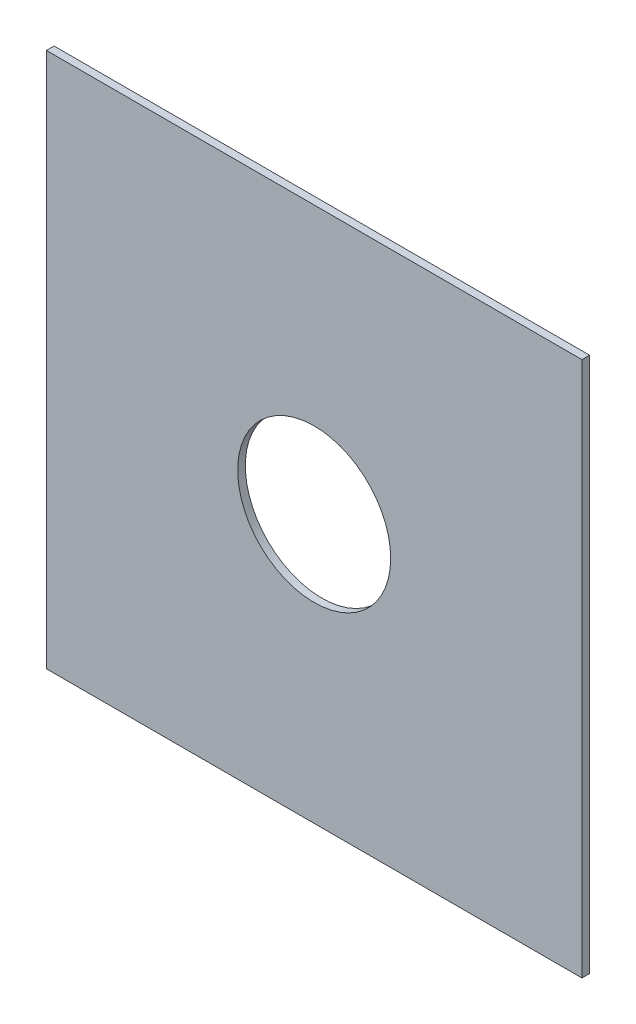
SolidWorks part; units mm, degrees
ref_plane "前视基准面" through (0, 0, 0) normal (0, 0, 1) x (1, 0, 0)
ref_plane "上视基准面" through (0, 0, 0) normal (0, 1, 0) x (1, 0, 0)
ref_plane "右视基准面" through (0, 0, 0) normal (1, 0, 0) x (0, 0, -1)
sketch "草图1" plane through (0, 0, 0) normal (0, 0, 1) x (1, 0, 0)
  line L0 (-49.8973, -319.1589) -> (650.1027, -319.1589) construction
  line L1 (-49.8973, 30.8411) -> (650.1027, 30.8411)
  line L2 (-49.8973, 30.8411) -> (-49.8973, -669.1589)
  line L3 (-49.8973, -669.1589) -> (650.1027, -669.1589)
  line L4 (650.1027, 30.8411) -> (650.1027, -669.1589)
  circle A0 centre (300.1027, -319.1589) radius 100
  dimension "D2" = 200
  dimension "D1" = 700
extrude "凸台-拉伸1" add sketch "草图1" along normal blind 10
